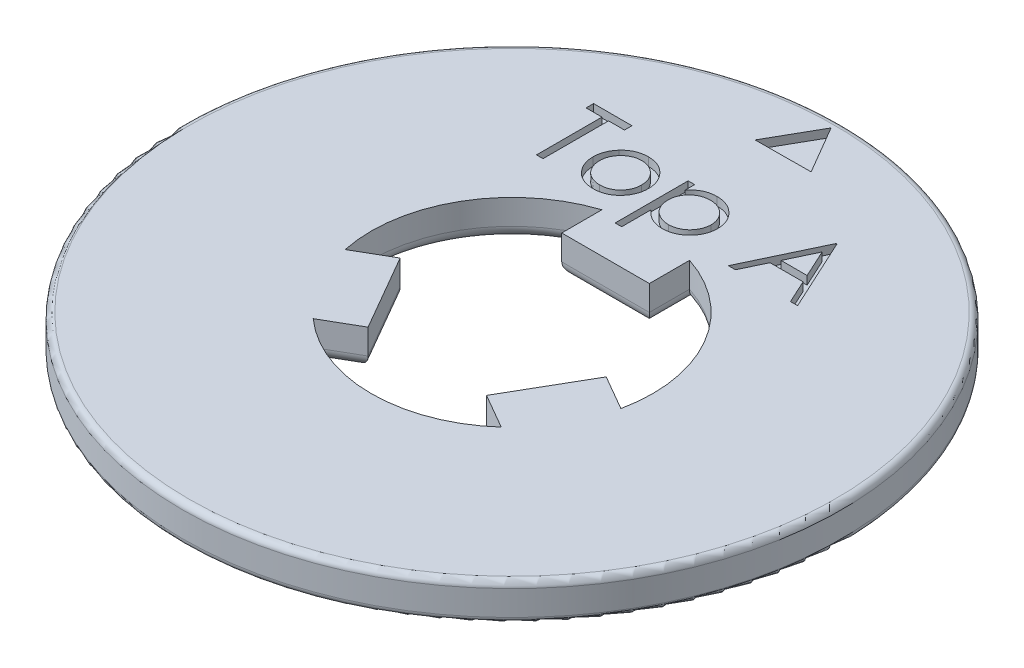
SolidWorks part; units mm, degrees
ref_plane "Front Plane" through (0, 0, 0) normal (0, 0, 1) x (1, 0, 0)
ref_plane "Top Plane" through (0, 0, 0) normal (0, 1, 0) x (1, 0, 0)
ref_plane "Right Plane" through (0, 0, 0) normal (1, 0, 0) x (0, 0, -1)
sketch "Sketch1" plane through (0, 0, 0) normal (0, 1, 0) x (1, 0, 0)
  line L0 (0, -15.8) -> (0, 15.8) construction
  line L1 (-15.8, 0) -> (15.8, 0) construction
  line L60 (6.6062, -1.3857) -> (4.9381, -0.4226)
  line L62 (-2.1031, 6.414) -> (-2.1031, 4.4878)
  line L63 (-2.1031, 4.4878) -> (2.0969, 4.4878)
  line L64 (2.0969, 6.416) -> (2.0969, 4.4878)
  line L68 (4.508, -5.024) -> (2.8381, -4.0599)
  line L69 (4.9381, -0.4226) -> (2.8381, -4.0599)
  line L70 (-4.5031, -5.0283) -> (-2.835, -4.0652)
  line L72 (-6.6049, -1.3921) -> (-4.935, -0.4279)
  line L73 (-2.835, -4.0652) -> (-4.935, -0.4279)
  circle A0 centre (0, 0) radius 15.8
  arc A5 (-2.1031, 6.414) -> (-6.6049, -1.3921) centre (0, 0) ccw
  arc A6 (-4.5031, -5.0283) -> (4.508, -5.024) centre (0, 0) ccw
  arc A7 (6.6062, -1.3857) -> (2.0969, 6.416) centre (0, 0) ccw
  point P3 (0, 9.9)
  point P11 (0, 6.1614)
  point P26 (0, 0)
  point P40 (0, 0)
  point P42 (0, 0)
  point P43 (0, 0)
  point P44 (0, 0)
  dimension "D6" = 3
  dimension "D5" = 4.2
extrude "Boss-Extrude1" add sketch "Sketch1" along normal blind 1.8
fillet "Fillet1" radius 0.3 2 edges at (0, 0, 15.8) (0, 1.8, 15.8)
ref_plane "Plane1" through (0, 1.8, 0) normal (0, 1, 0) x (1, 0, 0)
sketch "Sketch3" plane through (0, 1.8, 0) normal (0, 1, 0) x (1, 0, 0)
  line L0 (0, 0) -> (0, 13.6609) construction
  line L2 (-1.3308, 12.9858) -> (1.34, 13.0017)
  line L3 (1.34, 13.0017) -> (-0.0092, 15.3068)
  line L4 (-0.0092, 15.3068) -> (-1.3308, 12.9858)
  circle A0 centre (0, 13.7648) radius 0.771 construction
fillet "Fillet3" radius 0.6 12 edges at (5.7722, 0, 0.9041) (3.8881, 0, 2.2412) (3.6731, 0, 4.5419) (0.0033, 0, 6.75) (-3.6691, 0, 4.5468) (-5.7699, 0, 0.91) (-3.885, 0, 2.2466) (5.844, 0, -3.3778) (-2.1031, 0, -5.4509) (-0.0031, 0, -4.4878) (2.0969, 0, -5.4519) (-5.8473, 0, -3.3722)
extrude "Cut-Extrude1" cut sketch "Sketch3" against normal blind 0.4
sketch "Sketch4" plane through (0, 1.8, 0) normal (0, 1, 0) x (1, 0, 0)
  line L0 (-8.3279, 7.1231) -> (8.3197, 7.1231) construction
  text T0 "Top A"
extrude "Cut-Extrude2" cut sketch "Sketch4" against normal blind 0.4
scale "Scale1" scale about centroid uniform scaling yes scale factor 1.15
